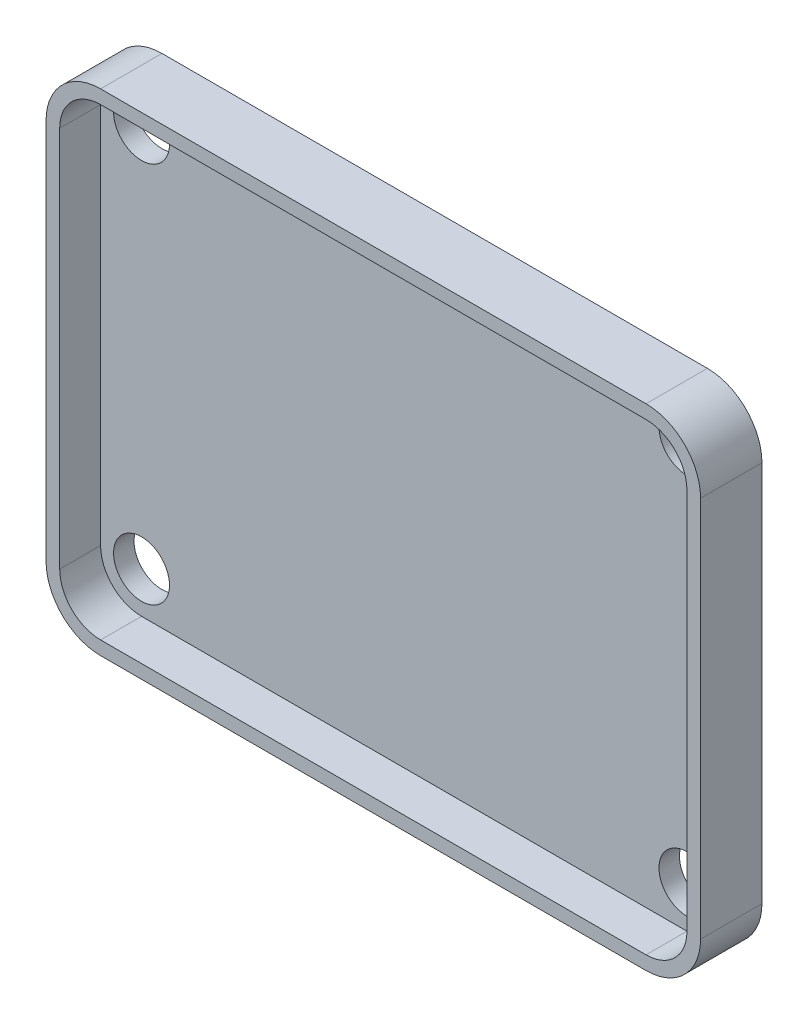
SolidWorks part; units mm, degrees
ref_plane "Front Plane" through (0, 0, 0) normal (0, 0, 1) x (1, 0, 0)
ref_plane "Top Plane" through (0, 0, 0) normal (0, 1, 0) x (1, 0, 0)
ref_plane "Right Plane" through (0, 0, 0) normal (1, 0, 0) x (0, 0, -1)
sketch "Sketch1" plane through (0, 0, 0) normal (0, 0, 1) x (1, 0, 0)
  line L1 (-20, -18) -> (20, -18)
  line L2 (-24, -14) -> (-24, 14)
  line L3 (-20, 18) -> (20, 18)
  line L4 (24, -14) -> (24, 14)
  line L5 (-24, -18) -> (24, 18) construction
  line L6 (-24, 18) -> (24, -18) construction
  arc A0 (-24, -14) -> (-20, -18) centre (-20, -14) ccw
  arc A1 (20, -18) -> (24, -14) centre (20, -14) ccw
  arc A2 (24, 14) -> (20, 18) centre (20, 14) ccw
  arc A3 (-20, 18) -> (-24, 14) centre (-20, 14) ccw
  circle A4 centre (-20, -14) radius 2.05
  circle A5 centre (-20, 14) radius 2.05
  circle A6 centre (20, 14) radius 2.05
  circle A7 centre (20, -14) radius 2.05
  point P0 (0, 0)
  dimension "D3" = 4
  dimension "D4" = 4
  dimension "D5" = 4
  dimension "D6" = 4
  dimension "D7" = 4.1
  dimension "D8" = 4.1
  dimension "D9" = 4.1
  dimension "D10" = 4.1
  dimension "D1" = 48
  dimension "D2" = 36
extrude "Boss-Extrude1" add sketch "Sketch1" along normal mid plane 4.5
sketch "Sketch3" plane through (0, 0, 2.25) normal (0, 0, 1) x (1, 0, 0)
  line L30 (23, -14) -> (23, 14)
  line L31 (20, 17) -> (-20, 17)
  line L32 (-23, 14) -> (-23, -14)
  line L33 (-20, -17) -> (20, -17)
  line L34 (23, -14) -> (23, 14)
  line L35 (20, 17) -> (-20, 17)
  line L36 (-23, 14) -> (-23, -14)
  line L37 (-20, -17) -> (20, -17)
  arc A24 (20, -17) -> (23, -14) centre (20, -14) ccw
  arc A25 (23, 14) -> (20, 17) centre (20, 14) ccw
  arc A26 (-20, 17) -> (-23, 14) centre (-20, 14) ccw
  arc A27 (-23, -14) -> (-20, -17) centre (-20, -14) ccw
  arc A28 (20, -17) -> (23, -14) centre (20, -14) ccw
  arc A29 (23, 14) -> (20, 17) centre (20, 14) ccw
  arc A30 (-20, 17) -> (-23, 14) centre (-20, 14) ccw
  arc A31 (-23, -14) -> (-20, -17) centre (-20, -14) ccw
  dimension "D1" = 1
extrude "Cut-Extrude2" cut sketch "Sketch3" against normal offset from surface (3 mm away) 1.5 up to face at (22.05, 14, -2.25)
